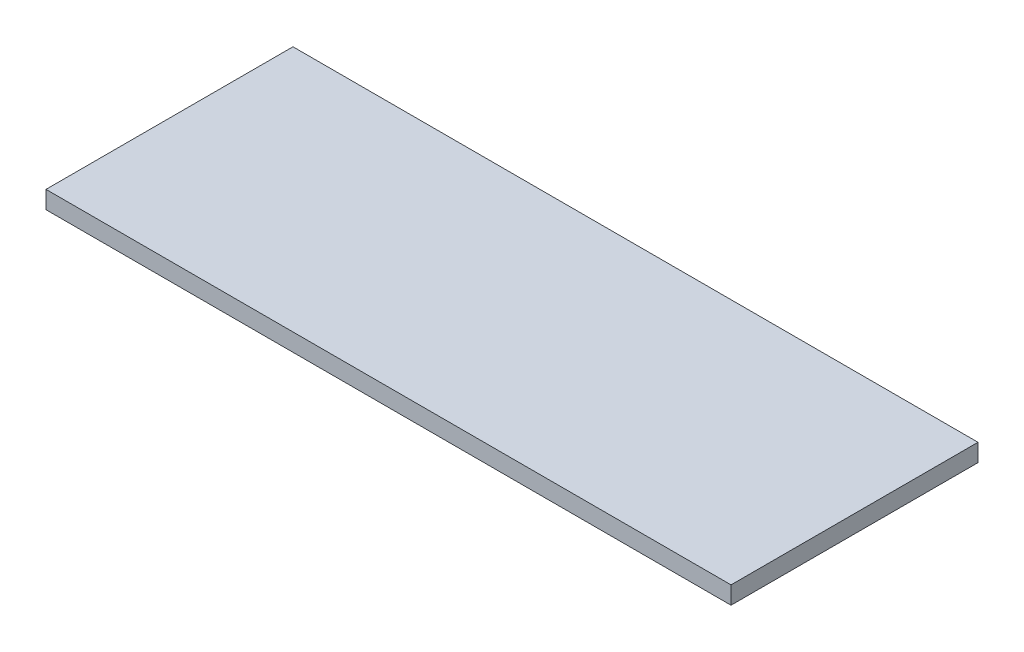
SolidWorks part; units mm, degrees
ref_plane "Front Plane" through (0, 0, 0) normal (0, 0, 1) x (1, 0, 0)
ref_plane "Top Plane" through (0, 0, 0) normal (0, 1, 0) x (1, 0, 0)
ref_plane "Right Plane" through (0, 0, 0) normal (1, 0, 0) x (0, 0, -1)
sketch "Sketch1" plane through (0, 0, 0) normal (0, 1, 0) x (1, 0, 0)
  line L1 (-58.25, -21) -> (58.25, -21)
  line L2 (-58.25, -21) -> (-58.25, 21)
  line L3 (-58.25, 21) -> (58.25, 21)
  line L4 (58.25, -21) -> (58.25, 21)
  line L5 (-58.25, -21) -> (58.25, 21) construction
  line L6 (-58.25, 21) -> (58.25, -21) construction
  point P0 (0, 0)
extrude "Boss-Extrude1" add sketch "Sketch1" along normal blind 3
